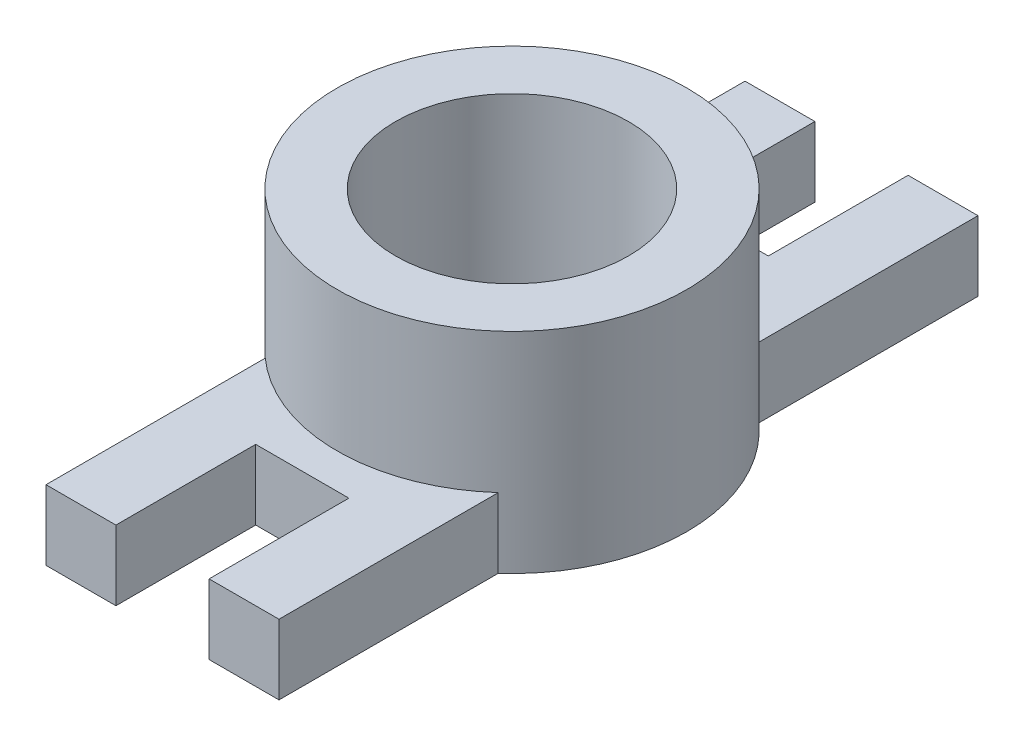
SolidWorks part; units mm, degrees
ref_plane "Front Plane" through (0, 0, 0) normal (0, 0, 1) x (1, 0, 0)
ref_plane "Top Plane" through (0, 0, 0) normal (0, 1, 0) x (1, 0, 0)
ref_plane "Right Plane" through (0, 0, 0) normal (1, 0, 0) x (0, 0, -1)
sketch "Sketch1" plane through (0, 0, 0) normal (0, 1, 0) x (1, 0, 0)
  line L0 (-25, 75) -> (-25, -75)
  line L1 (-55, 0) -> (55, 0) construction
  line L2 (-25, 75) -> (-10, 75)
  line L3 (-10, 75) -> (-10, 45)
  line L4 (-10, 45) -> (10, 45)
  line L5 (10, 45) -> (10, 75)
  line L6 (10, 75) -> (25, 75)
  line L7 (25, 75) -> (25, -75)
  line L8 (-88.4613, 0) -> (104.954, 0) construction
  line L9 (10, -75) -> (25, -75)
  line L10 (10, -45) -> (10, -75)
  line L11 (-10, -45) -> (10, -45)
  line L12 (-10, -75) -> (-10, -45)
  line L13 (-25, -75) -> (-10, -75)
  point P12 (25, 0)
  point P20 (-25, 0)
  dimension "D1" = 75
  dimension "D2" = 15
  dimension "D3" = 30
  dimension "D4" = 20
  dimension "D5" = 25
extrude "Boss-Extrude1" add sketch "Sketch1" along normal blind 15
sketch "Sketch3" plane through (0, 0, 0) normal (0, -1, 0) x (1, 0, 0)
  circle A0 centre (0, 0) radius 37.5
  circle A1 centre (0, 0) radius 25
  dimension "D1" = 75
  dimension "D2" = 50
extrude "Boss-Extrude2" add sketch "Sketch3" against normal blind 45
sketch "Sketch4" plane through (0, 15, 0) normal (0, 1, 0) x (1, 0, 0)
  circle A0 centre (0, 0) radius 25
extrude "Cut-Extrude1" cut sketch "Sketch4" against normal blind 45
